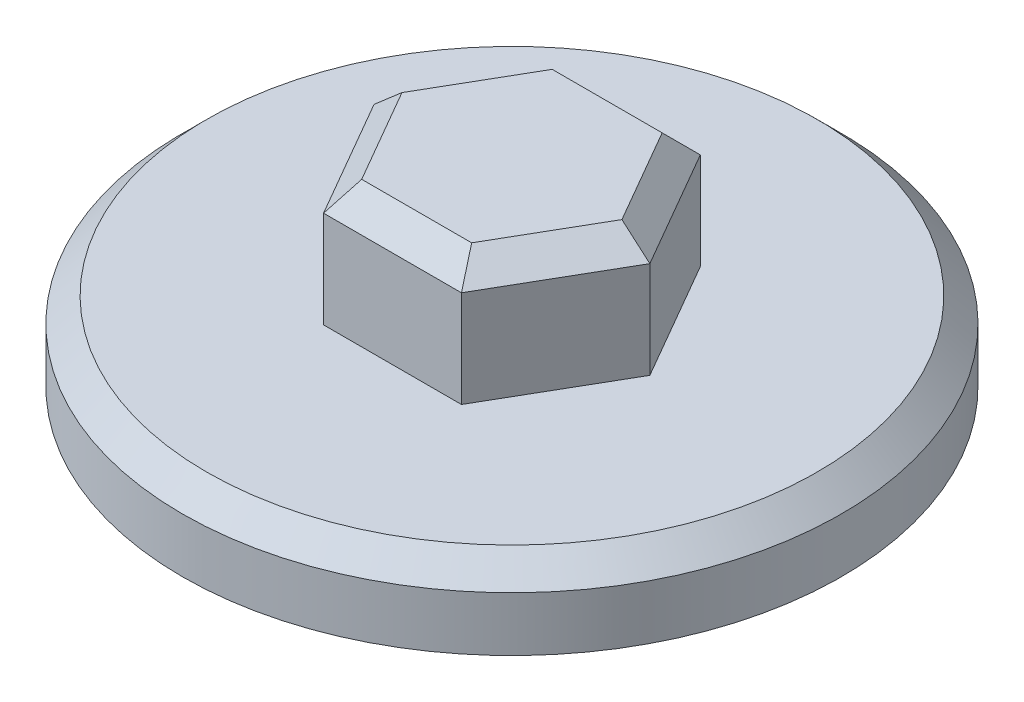
SolidWorks part; units mm, degrees
ref_plane "Płaszczyzna przednia" through (0, 0, 0) normal (0, 0, 1) x (1, 0, 0)
ref_plane "Płaszczyzna górna" through (0, 0, 0) normal (0, 1, 0) x (1, 0, 0)
ref_plane "Płaszczyzna prawa" through (0, 0, 0) normal (1, 0, 0) x (0, 0, -1)
sketch "Szkic1" plane through (0, 0, 0) normal (0, 1, 0) x (1, 0, 0)
  circle A0 centre (0, 0) radius 5.45
  dimension "D1" = 10.9
extrude "Dodanie-wyciągnięcie1" add sketch "Szkic1" along normal blind 1.3
sketch "Szkic2" plane through (0, 1.3, 0) normal (0, 1, 0) x (1, 0, 0)
  line L1 (2.2805, 0) -> (1.1403, 1.975)
  line L2 (1.1403, 1.975) -> (-1.1403, 1.975)
  line L3 (-1.1403, 1.975) -> (-2.2805, 0)
  line L4 (-2.2805, 0) -> (-1.1403, -1.975)
  line L5 (-1.1403, -1.975) -> (1.1403, -1.975)
  line L6 (1.1403, -1.975) -> (2.2805, 0)
  circle A0 centre (0, 0) radius 1.975 construction
  dimension "D1" = 3.95
extrude "Dodanie-wyciągnięcie2" add sketch "Szkic2" along normal blind 2
chamfer "Sfazowanie1" distance 0.4 angle 45 7 edges at (0, 1.3, 5.45) (0, 3.3, 1.975) (-1.7104, 3.3, 0.9875) (-1.7104, 3.3, -0.9875) (0, 3.3, -1.975) (1.7104, 3.3, -0.9875) (1.7104, 3.3, 0.9875)
